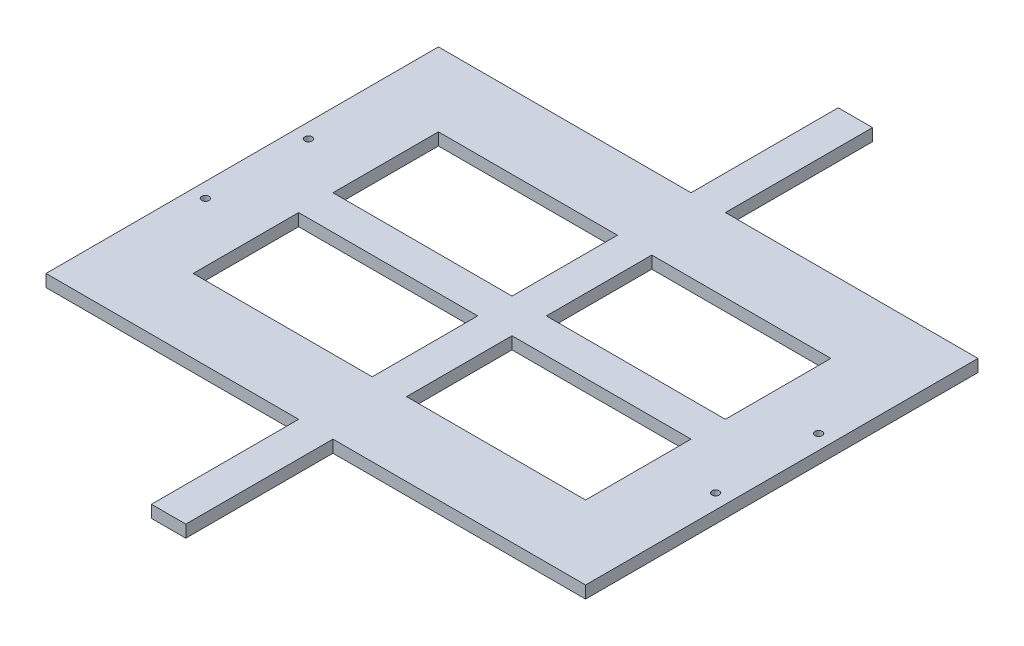
SolidWorks part; units mm, degrees
ref_plane "Front Plane" through (0, 0, 0) normal (0, 0, 1) x (1, 0, 0)
ref_plane "Top Plane" through (0, 0, 0) normal (0, 1, 0) x (1, 0, 0)
ref_plane "Right Plane" through (0, 0, 0) normal (1, 0, 0) x (0, 0, -1)
sketch "Sketch1" plane through (0, 0, 0) normal (0, 1, 0) x (1, 0, 0)
  line L0 (-30, 30) -> (190, 30)
  line L1 (0, 0) -> (160, 0)
  line L2 (0, 0) -> (0, -100)
  line L3 (0, -100) -> (160, -100)
  line L4 (160, 0) -> (160, -100)
  line L5 (190, 30) -> (190, -130)
  line L6 (-30, -130) -> (190, -130)
  line L7 (-30, 30) -> (-30, -130)
  line L9 (73, 0) -> (87, 0)
  line L10 (73, 0) -> (73, -100)
  line L11 (73, -100) -> (87, -100)
  line L12 (87, 0) -> (87, -100)
  line L13 (0, -43) -> (160, -43)
  line L14 (0, -43) -> (0, -57)
  line L15 (0, -57) -> (160, -57)
  line L16 (160, -43) -> (160, -57)
  dimension "D1" = 160
  dimension "D2" = 100
  dimension "D4" = 14
  dimension "D5" = 14
  dimension "D6" = 43
  dimension "D7" = 73
  dimension "D3" = 30
extrude "Boss-Extrude1" add sketch "Sketch1" along normal blind 5 contours L0 L7 L6 L5 L1 L4 L3 L2 | L2 L15 L10 L13 | L12 L15 L4 L13 | L10 L13 L12 L1 | L15 L10 L3 L12 | L10 L15 L12 L13
sketch "Sketch2" plane through (0, 5, 0) normal (0, 1, 0) x (1, 0, 0)
  line L0 (-30, -50) -> (190, -50) construction
  line L1 (-30, 30) -> (-30, -130) construction
  line L2 (190, 30) -> (190, -130) construction
  line L3 (80, 30) -> (80, -134.4424) construction
  line L4 (-30, 30) -> (190, 30) construction
  circle A0 centre (-24, -29) radius 1.5
  circle A1 centre (-24, -71) radius 1.5
  circle A2 centre (184, -29) radius 1.5
  circle A3 centre (184, -71) radius 1.5
  dimension "D1" = 3
  dimension "D2" = 21
  dimension "D3" = 6
extrude "Cut-Extrude1" cut sketch "Sketch2" against normal blind 5
sketch "Sketch3" plane through (0, 5, 0) normal (0, 1, 0) x (1, 0, 0)
  line L0 (-30, 30) -> (190, 30) construction
  line L1 (73, 90) -> (87, 90)
  line L2 (73, 90) -> (73, 30)
  line L3 (73, 30) -> (87, 30)
  line L4 (87, 90) -> (87, 30)
  line L5 (-30, -50) -> (190, -50) construction
  line L6 (-30, 30) -> (-30, -130) construction
  line L7 (190, 30) -> (190, -130) construction
  line L8 (80, 30) -> (80, -130) construction
  line L9 (-30, -130) -> (190, -130) construction
  line L10 (73, -190) -> (87, -190)
  line L11 (87, -190) -> (87, -130)
  line L12 (73, -190) -> (73, -130)
  line L13 (73, -130) -> (87, -130)
  dimension "D1" = 14
  dimension "D2" = 60
  dimension "D3" = 110
extrude "Boss-Extrude2" add sketch "Sketch3" against normal blind 5
equation "\"D5@Sketch1\"=\"D4@Sketch1\""
